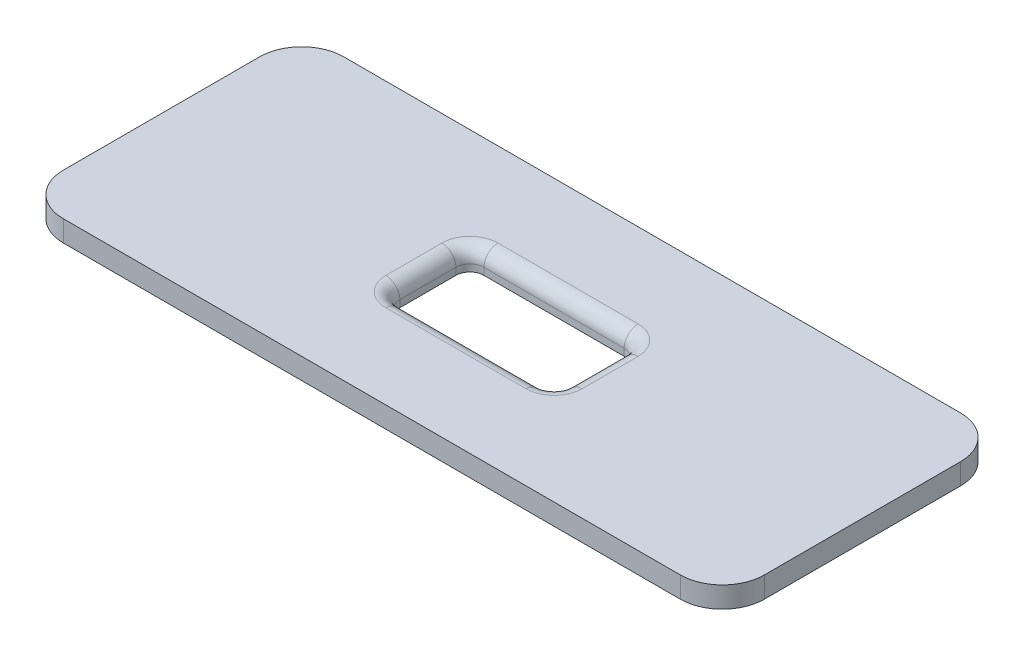
SolidWorks part; units mm, degrees
ref_plane "Front Plane" through (0, 0, 0) normal (0, 0, 1) x (1, 0, 0)
ref_plane "Top Plane" through (0, 0, 0) normal (0, 1, 0) x (1, 0, 0)
ref_plane "Right Plane" through (0, 0, 0) normal (1, 0, 0) x (0, 0, -1)
sketch "Sketch1" plane through (0, 0, 0) normal (0, 1, 0) x (1, 0, 0)
  line L1 (-22, 10) -> (22, 10)
  line L2 (-25, 7) -> (-25, -7)
  line L3 (-22, -10) -> (22, -10)
  line L4 (25, 7) -> (25, -7)
  line L5 (-25, 10) -> (25, -10) construction
  line L6 (-25, -10) -> (25, 10) construction
  line L7 (-5, 3) -> (5, 3)
  line L8 (-6, 2) -> (-6, -2)
  line L9 (-5, -3) -> (5, -3)
  line L10 (6, 2) -> (6, -2)
  line L11 (-6, 3) -> (6, -3) construction
  line L12 (-6, -3) -> (6, 3) construction
  arc A0 (25, 7) -> (22, 10) centre (22, 7) ccw
  arc A1 (22, -10) -> (25, -7) centre (22, -7) ccw
  arc A2 (-22, -10) -> (-25, -7) centre (-22, -7) cw
  arc A3 (-25, 7) -> (-22, 10) centre (-22, 7) cw
  arc A4 (5, 3) -> (6, 2) centre (5, 2) cw
  arc A5 (6, -2) -> (5, -3) centre (5, -2) cw
  arc A6 (-5, -3) -> (-6, -2) centre (-5, -2) cw
  arc A7 (-6, 2) -> (-5, 3) centre (-5, 2) cw
  point P0 (0, 0)
  point P6 (0, 0)
  dimension "D5" = 3
  dimension "D6" = 1
  dimension "D1" = 50
  dimension "D2" = 20
  dimension "D3" = 12
  dimension "D4" = 6
extrude "Boss-Extrude1" add sketch "Sketch1" along normal blind 1.5
fillet "Fillet1" radius 1 8 edges at (-5.7071, 1.5, 2.7071) (-6, 1.5, 0) (-5.7071, 1.5, -2.7071) (0, 1.5, -3) (5.7071, 1.5, -2.7071) (6, 1.5, 0) (5.7071, 1.5, 2.7071) (0, 1.5, 3)
